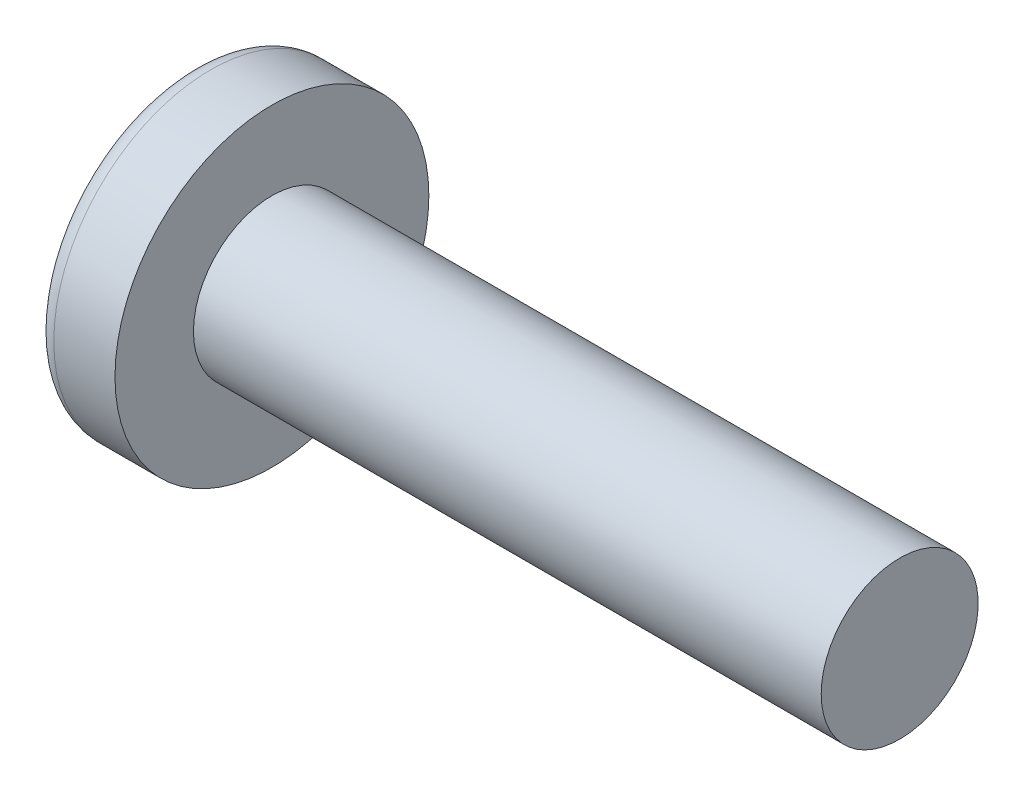
SolidWorks part; units mm, degrees
ref_plane "Plane1" through (0, 0, 0) normal (0, 0, 1) x (1, 0, 0)
ref_plane "Plane2" through (0, 0, 0) normal (0, 1, 0) x (1, 0, 0)
ref_plane "Plane3" through (0, 0, 0) normal (1, 0, 0) x (0, 0, -1)
sketch "BodySke" plane through (0, 0, 0) normal (0, 0, 1) x (1, 0, 0)
  line L0 (1.6, 1) -> (1.6, 2)
  line L1 (2, 6.35) -> (2, -3.175) construction
  line L2 (-25.4, 0) -> (127, 0) construction
  line L3 (9.6, 0) -> (0, 0)
  line L4 (1.6, 1) -> (9.6, 1)
  line L5 (9.6, 1) -> (9.6, 0)
  line L6 (0.8201, 2) -> (1.6, 2)
  line L7 (1.6, -1) -> (9.6, -1) construction
  line L8 (1.6, 6.35) -> (1.6, -3.175) construction
  arc A0 (0.6271, 1.9027) -> (0, 0) centre (3.2, 0) ccw
  arc A2 (0.6271, 1.9027) -> (0.8201, 2) centre (0.8201, 1.76) cw
  dimension "Head_crown_rad" = 3.2
  dimension "Head_fillet_rad" = 0.24
  dimension "Diameter" = 2
  dimension "Length" = 8
  dimension "Head_ht" = 1.6
  dimension "Head_dia" = 4
  dimension "Advance" = 0.4
  dimension "Thread_nom" = 8
revolve "Base-Revolve" add sketch "BodySke" angle 360 about L2
cosmetic thread "ThreadCosmetic" [suppressed] parameters "Thread_length"=12.2, "Thread_minor"=1.548
sketch "Sketch3" plane through (0, 0, 0) normal (1, 0, 0) x (0, 0, -1)
  line L0 (0.5, 0.63) -> (0.02, 0.63)
  line L1 (0.5, 0.63) -> (0.5, 2.45)
  line L2 (0.02, 2.45) -> (0.5, 2.45)
  line L3 (0.02, 2.45) -> (0.02, 0.63)
  dimension "Cross_dia" = 1.82
  dimension "D1" = 2.45
  dimension "Cross_width" = 0.48
  dimension "D2" = 0.5
ref_plane "Plane4" through (1.19, 0, 0) normal (1, 0, 0) x (0, 0, -1)
sketch "Sketch4" plane through (1.19, 0, 0) normal (1, 0, 0) x (0, 0, -1)
  line L0 (0.25, -0.25) -> (-0.25, -0.25)
  line L1 (0.25, -0.25) -> (0.25, 0.25)
  line L2 (-0.25, 0.25) -> (0.25, 0.25)
  line L3 (-0.25, 0.25) -> (-0.25, -0.25)
  dimension "D2" = 0.5
  dimension "D1" = 0.5
  dimension "D3" = 0.25
  dimension "D4" = 0.25
loft "Cut-Loft1" cut profiles "Sketch3", "Sketch4"
pattern_circular "CirPattern1" count 4 every 90 about axis through (0, 0, 0) along (1, 0, 0) of "Cut-Loft1"
sketch "ThdSchSke" plane through (0, 0, 0) normal (0, 0, 1) x (1, 0, 0)
  line L0 (4.5, -2.055) -> (4.1884, -2.5)
  line L1 (4.5, -2.055) -> (4.8116, -2.5)
  line L2 (4.8116, -2.5) -> (4.8116, -3.125)
  line L3 (-3.175, 0) -> (5.1513, 0) construction
  line L5 (4.8116, -3.125) -> (4.1884, -3.125)
  line L6 (4.1884, -3.125) -> (4.1884, -2.5)
  dimension "SideAngle" = 55
  dimension "VeeAngle" = 70
  dimension "Thread_minor" = 4.11
  dimension "Overcut" = 6.25
  dimension "Diameter" = 5
  dimension "Start" = 4.5
revolve "ThreadSchematic" [suppressed] cut sketch "ThdSchSke" angle 360 about L3
pattern_linear "ThdSchPat" [suppressed]
equation "\"D1@Sketch3\" = \"Cross_dia@Sketch3\" / 2"
equation "\"D2@Sketch3\" = \"Cross_width@Sketch3\" / 2"
equation "\"D1@Sketch4\" = \"Cross_width@Sketch3\" *.5"
equation "\"D2@Sketch4\" = \"D1@Sketch4\""
equation "\"D3@Sketch4\" = \"D1@Sketch4\" / 2"
equation "\"D4@Sketch4\" = \"D2@Sketch4\" / 2"
equation "\"Thread_length@ThreadCosmetic\" = ((sgn( (\"Length@BodySke\" - \"Advance@BodySke\" ) - \"Thread_nom@BodySke\" )-1)*( (\"Length@BodySke\" - \"Advance@BodySke\" ) - \"Thread_nom@BodySke\" ))/-2+ \"Thread_nom@BodySke\""
equation "\"Thread_minor@ThdSchSke\" = \"Thread_minor@ThreadCosmetic\""
equation "\"Diameter@ThdSchSke\" = \"Diameter@BodySke\""
equation "\"Overcut@ThdSchSke\" = \"Diameter@BodySke\" * 1.25"
equation "\"Start@ThdSchSke\" = \"Head_ht@BodySke\" + \"Length@BodySke\" - \"Thread_length@ThreadCosmetic\"  '---Non-countersunk---"
equation "\"Num_threads@ThdSchPat\" = int( \"Thread_length@ThreadCosmetic\" / \"Advance@BodySke\" + 0.999 )  + 1"
equation "\"Advance@ThdSchPat\" = \"Thread_length@ThreadCosmetic\" /  (\"Num_threads@ThdSchPat\" - 1) 'relax it"
